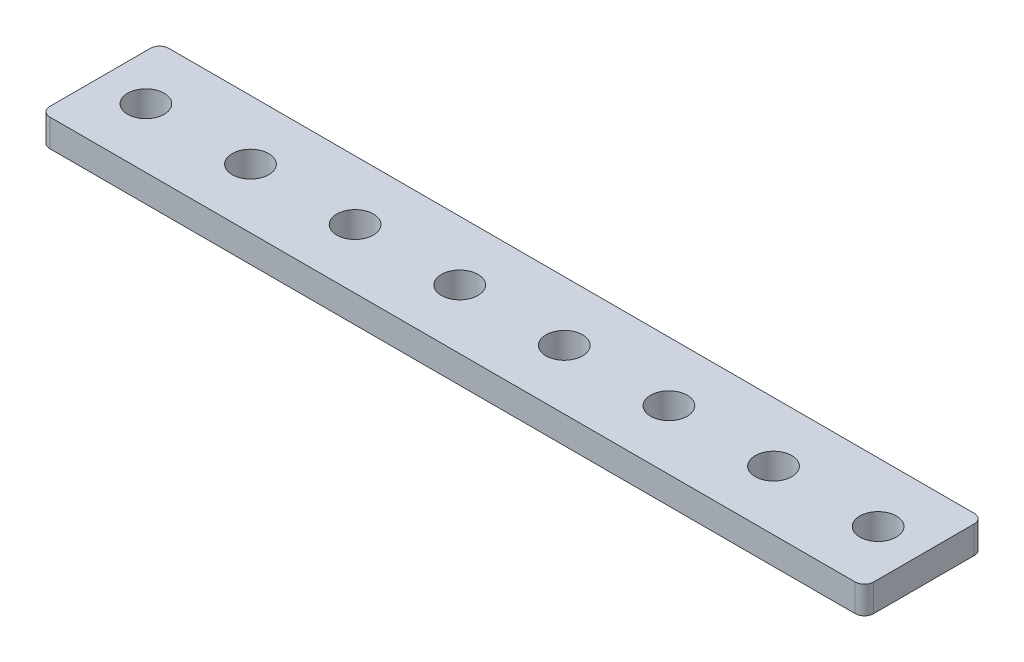
SolidWorks part; units mm, degrees
ref_plane "Front Plane" through (0, 0, 0) normal (0, 0, 1) x (1, 0, 0)
ref_plane "Top Plane" through (0, 0, 0) normal (0, 1, 0) x (1, 0, 0)
ref_plane "Right Plane" through (0, 0, 0) normal (1, 0, 0) x (0, 0, -1)
sketch "Sketch1" plane through (0, 0, 0) normal (0, 1, 0) x (1, 0, 0)
  line L1 (-44, -6.5) -> (44, -6.5)
  line L2 (-45, -5.5) -> (-45, 5.5)
  line L3 (-44, 6.5) -> (44, 6.5)
  line L4 (45, -5.5) -> (45, 5.5)
  line L5 (-45, -6.5) -> (45, 6.5) construction
  line L6 (-45, 6.5) -> (45, -6.5) construction
  arc A0 (44, -6.5) -> (45, -5.5) centre (44, -5.5) ccw
  arc A1 (44, 6.5) -> (45, 5.5) centre (44, 5.5) cw
  arc A2 (-45, 5.5) -> (-44, 6.5) centre (-44, 5.5) cw
  arc A3 (-44, -6.5) -> (-45, -5.5) centre (-44, -5.5) cw
  point P0 (0, 0)
  dimension "D1" = 1
extrude "Boss-Extrude1" add sketch "Sketch1" along normal blind 3
sketch "Sketch2" plane through (0, 3, 0) normal (0, 1, 0) x (1, 0, 0)
  line L0 (-45, 0) -> (45, 0) construction
  line L1 (-45, 5.5) -> (-45, -5.5) construction
  line L2 (45, -5.5) -> (45, 5.5) construction
sketch "Sketch3" plane through (0, 3, 0) normal (0, 1, 0) x (1, 0, 0)
  line L0 (0, -6.5) -> (0, 6.5) construction
  line L1 (-44, -6.5) -> (44, -6.5) construction
  line L2 (44, 6.5) -> (-44, 6.5) construction
  line L3 (-45, 0) -> (-40, 0) construction
  line L4 (-45, 5.5) -> (-45, -5.5) construction
  line L5 (-45, 0) -> (45, 0) construction
  circle A0 centre (-40, 0) radius 2
  circle A1 centre (-28.5714, 0) radius 2
  circle A2 centre (-17.1429, 0) radius 2
  circle A3 centre (-5.7143, 0) radius 2
  circle A4 centre (5.7143, 0) radius 2
  circle A5 centre (17.1429, 0) radius 2
  circle A6 centre (28.5714, 0) radius 2
  circle A7 centre (40, 0) radius 2
  dimension "D1" = 8
extrude "Cut-Extrude1" cut sketch "Sketch3" against normal through all
